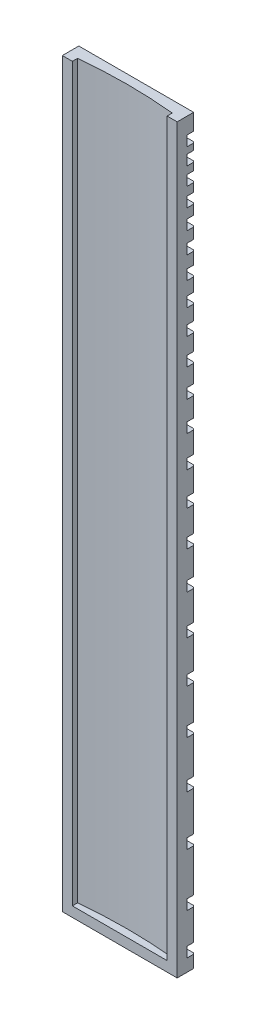
SolidWorks part; units mm, degrees
ref_plane "Front Plane" through (0, 0, 0) normal (0, 0, 1) x (1, 0, 0)
ref_plane "Top Plane" through (0, 0, 0) normal (0, 1, 0) x (1, 0, 0)
ref_plane "Right Plane" through (0, 0, 0) normal (1, 0, 0) x (0, 0, -1)
sketch "Sketch1" plane through (0, 0, 0) normal (0, 0, 1) x (1, 0, 0)
  line L0 (0, 464.91) -> (0, -53.7621) construction
  line L1 (207.2765, 0) -> (-181.268, 0) construction
  line L2 (23.8804, 464.91) -> (23.8804, -53.7621) construction
  line L3 (-23.8804, 464.91) -> (-23.8804, -53.7621) construction
  line L4 (16.5652, 464.91) -> (16.5652, -53.7621) construction
  line L5 (-16.5652, 464.91) -> (-16.5652, -53.7621) construction
  line L6 (-39.4637, 452.8091) -> (40.6786, 452.8091) construction
  line L7 (40.6786, 4) -> (-39.4637, 4) construction
  line L8 (-16.5652, 4) -> (-23.8804, 452.8091) construction
  line L9 (23.8804, 452.8091) -> (16.5652, 4) construction
  line L10 (-39.4637, 442.2134) -> (40.6786, 442.2134) construction
  line L11 (40.6786, 31.6398) -> (-39.4637, 31.6398) construction
  line L12 (40.6786, 430.9875) -> (-39.4637, 430.9875) construction
  line L13 (-39.4637, 455.3091) -> (40.6786, 455.3091)
  line L14 (-39.4637, 65.2793) -> (40.6786, 65.2793) construction
  line L15 (-39.4637, 364.0154) -> (40.6786, 364.0154) construction
  line L16 (-39.4637, 444.7134) -> (40.6786, 444.7134)
  line L17 (-39.4637, 61.2793) -> (40.6786, 61.2793)
  line L18 (-39.4637, 97.0308) -> (40.6786, 97.0308) construction
  line L19 (-39.4637, 93.0308) -> (40.6786, 93.0308)
  line L20 (40.6786, 127.0002) -> (-39.4637, 127.0002) construction
  line L21 (-39.4637, 67.7793) -> (40.6786, 67.7793)
  line L22 (-39.4637, 155.2875) -> (40.6786, 155.2875) construction
  line L23 (-39.4637, 366.5154) -> (40.6786, 366.5154)
  line L24 (40.6786, 181.9872) -> (-39.4637, 181.9872) construction
  line L25 (-39.4637, 99.5308) -> (40.6786, 99.5308)
  line L26 (-39.4637, 207.1884) -> (40.6786, 207.1884) construction
  line L27 (-39.4637, 151.2875) -> (40.6786, 151.2875)
  line L28 (40.6786, 230.9751) -> (-39.4637, 230.9751) construction
  line L29 (-39.4637, 157.7875) -> (40.6786, 157.7875)
  line L30 (-39.4637, 253.4267) -> (40.6786, 253.4267) construction
  line L31 (-39.4637, 203.1883) -> (40.6786, 203.1883)
  line L32 (40.6786, 274.6183) -> (-39.4637, 274.6183) construction
  line L33 (-39.4637, 209.6884) -> (40.6786, 209.6884)
  line L34 (-39.4637, 294.6205) -> (40.6786, 294.6205) construction
  line L35 (-39.4637, 249.4267) -> (40.6786, 249.4267)
  line L36 (40.6786, 313.5) -> (-39.4637, 313.5) construction
  line L37 (-39.4637, 255.9267) -> (40.6786, 255.9267)
  line L38 (-39.4637, 331.3199) -> (40.6786, 331.3199) construction
  line L39 (-39.4637, 290.6205) -> (40.6786, 290.6205)
  line L40 (40.6786, 348.1397) -> (-39.4637, 348.1397) construction
  line L41 (-39.4637, 297.1205) -> (40.6786, 297.1205)
  line L42 (-39.4637, 379.0001) -> (40.6786, 379.0001) construction
  line L43 (-39.4637, 327.3199) -> (40.6786, 327.3199)
  line L44 (40.6786, 393.1438) -> (-39.4637, 393.1437) construction
  line L45 (-39.4637, 333.8199) -> (40.6786, 333.8199)
  line L46 (-39.4637, 406.4936) -> (40.6786, 406.4936) construction
  line L47 (-39.4637, 360.0154) -> (40.6786, 360.0154)
  line L48 (40.6786, 419.0942) -> (-39.4637, 419.0942) construction
  line L49 (-39.4637, 381.5001) -> (40.6786, 381.5001)
  line L50 (-39.4637, 375.0001) -> (40.6786, 375.0001)
  line L51 (-39.4637, 408.9936) -> (40.6786, 408.9936)
  line L52 (-39.4637, 402.4936) -> (40.6786, 402.4936)
  line L53 (-39.4637, 438.2134) -> (40.6786, 438.2134)
  line L54 (-39.4637, 448.8091) -> (40.6786, 448.8091)
  line L55 (40.6786, 34.1398) -> (-39.4637, 34.1398)
  line L56 (40.6786, 433.4875) -> (-39.4637, 433.4875)
  line L57 (40.6786, 426.9875) -> (-39.4637, 426.9875)
  line L58 (40.6786, 415.0942) -> (-39.4637, 415.0942)
  line L59 (40.6786, 389.1438) -> (-39.4637, 389.1438)
  line L60 (40.6786, 129.5002) -> (-39.4637, 129.5002)
  line L61 (40.6786, 344.1397) -> (-39.4637, 344.1397)
  line L62 (40.6786, 184.4872) -> (-39.4637, 184.4872)
  line L63 (40.6786, 309.5) -> (-39.4637, 309.5)
  line L64 (40.6786, 233.4751) -> (-39.4637, 233.4751)
  line L65 (40.6786, 270.6183) -> (-39.4637, 270.6183)
  line L66 (40.6786, 277.1183) -> (-39.4637, 277.1183)
  line L67 (40.6786, 226.9751) -> (-39.4637, 226.9751)
  line L68 (40.6786, 316) -> (-39.4637, 316)
  line L69 (40.6786, 177.9872) -> (-39.4637, 177.9872)
  line L70 (40.6786, 350.6397) -> (-39.4637, 350.6397)
  line L71 (40.6786, 123.0002) -> (-39.4637, 123.0002)
  line L72 (40.6786, 395.6438) -> (-39.4637, 395.6438)
  line L73 (40.6786, 27.6398) -> (-39.4637, 27.6398)
  line L74 (40.6786, 421.5942) -> (-39.4637, 421.5942)
  line L75 (40.6786, 1.5) -> (-39.4637, 1.5)
  line L76 (40.6786, 8) -> (-39.4637, 8)
  line L77 (40.6786, 1.5) -> (40.6786, 8)
  line L78 (40.6786, 448.8091) -> (40.6786, 455.3091)
  line L79 (40.6786, 438.2134) -> (40.6786, 444.7134)
  line L80 (40.6786, 426.9875) -> (40.6786, 433.4875)
  line L81 (40.6786, 415.0942) -> (40.6786, 421.5942)
  line L82 (40.6786, 402.4936) -> (40.6786, 408.9936)
  line L83 (40.6786, 389.1438) -> (40.6786, 395.6438)
  line L84 (40.6786, 375.0001) -> (40.6786, 381.5001)
  line L85 (40.6786, 360.0154) -> (40.6786, 366.5154)
  line L86 (40.6786, 344.1397) -> (40.6786, 350.6397)
  line L87 (40.6786, 327.3199) -> (40.6786, 333.8199)
  line L88 (40.6786, 309.5) -> (40.6786, 316)
  line L89 (40.6786, 290.6205) -> (40.6786, 297.1205)
  line L90 (40.6786, 270.6183) -> (40.6786, 277.1183)
  line L91 (40.6786, 249.4267) -> (40.6786, 255.9267)
  line L92 (40.6786, 226.9751) -> (40.6786, 233.4751)
  line L93 (40.6786, 203.1883) -> (40.6786, 209.6884)
  line L94 (40.6786, 177.9872) -> (40.6786, 184.4872)
  line L95 (40.6786, 151.2875) -> (40.6786, 157.7875)
  line L96 (40.6786, 123.0002) -> (40.6786, 129.5002)
  line L97 (40.6786, 93.0308) -> (40.6786, 99.5308)
  line L98 (40.6786, 61.2793) -> (40.6786, 67.7793)
  line L99 (40.6786, 27.6398) -> (40.6786, 34.1398)
  line L100 (-39.4637, 1.5) -> (-39.4637, 8)
  line L101 (-39.4637, 448.8091) -> (-39.4637, 455.3091)
  line L102 (-39.4637, 438.2134) -> (-39.4637, 444.7134)
  line L103 (-39.4637, 426.9875) -> (-39.4637, 433.4875)
  line L104 (-39.4637, 415.0942) -> (-39.4637, 421.5942)
  line L105 (-39.4637, 402.4936) -> (-39.4637, 408.9936)
  line L106 (-39.4637, 389.1438) -> (-39.4637, 395.6438)
  line L107 (-39.4637, 375.0001) -> (-39.4637, 381.5001)
  line L108 (-39.4637, 360.0154) -> (-39.4637, 366.5154)
  line L109 (-39.4637, 344.1397) -> (-39.4637, 350.6397)
  line L110 (-39.4637, 327.3199) -> (-39.4637, 333.8199)
  line L111 (-39.4637, 309.5) -> (-39.4637, 316)
  line L112 (-39.4637, 290.6205) -> (-39.4637, 297.1205)
  line L113 (-39.4637, 270.6183) -> (-39.4637, 277.1183)
  line L114 (-39.4637, 249.4267) -> (-39.4637, 255.9267)
  line L115 (-39.4637, 226.9751) -> (-39.4637, 233.4751)
  line L116 (-39.4637, 203.1883) -> (-39.4637, 209.6884)
  line L117 (-39.4637, 177.9872) -> (-39.4637, 184.4872)
  line L118 (-39.4637, 151.2875) -> (-39.4637, 157.7875)
  line L119 (-39.4637, 123.0002) -> (-39.4637, 129.5002)
  line L120 (-39.4637, 93.0308) -> (-39.4637, 99.5308)
  line L121 (-39.4637, 61.2793) -> (-39.4637, 67.7793)
  line L122 (-39.4637, 27.6398) -> (-39.4637, 34.1398)
  dimension "D7" = 2.5
  dimension "D31" = 6.5
  dimension "D1" = 23.8804
  dimension "D2" = 23.8804
  dimension "D3" = 16.5652
  dimension "D4" = 16.5652
  dimension "D5" = 452.8091
  dimension "D6" = 4
  dimension "D9" = 6.5
  dimension "D10" = 31.6398
  dimension "D11" = 65.2793
  dimension "D12" = 97.0308
  dimension "D13" = 127.0002
  dimension "D14" = 155.2875
  dimension "D15" = 181.9872
  dimension "D16" = 207.1884
  dimension "D17" = 230.9751
  dimension "D18" = 253.4267
  dimension "D19" = 274.6183
  dimension "D20" = 294.6205
  dimension "D21" = 313.5
  dimension "D22" = 331.3199
  dimension "D23" = 348.1397
  dimension "D24" = 442.2134
  dimension "D25" = 430.9875
  dimension "D26" = 419.0942
  dimension "D27" = 406.4936
  dimension "D28" = 393.1438
  dimension "D29" = 379.0001
  dimension "D30" = 364.0154
  dimension "D33" = 6.5
  dimension "D8" = 2.5
  dimension "D32" = 2.5
sketch "Sketch2" plane through (0, 0, 0) normal (0, 0, 1) x (1, 0, 0)
  line L0 (30.163, 490.1178) -> (30.163, -68.1918) construction
  line L1 (-30.163, 490.1178) -> (-30.163, -68.1918) construction
  line L2 (0, 464.91) -> (0, -53.7621) construction
  line L3 (36.563, -68.1918) -> (36.563, 490.1178) construction
  line L4 (-36.563, 490.1178) -> (-36.563, -68.1918) construction
  line L5 (-36.563, 0) -> (36.563, 0)
  line L6 (207.2765, 0) -> (-181.268, 0) construction
  line L7 (36.563, 0) -> (36.563, 465.7035)
  line L8 (36.563, 465.7035) -> (-36.563, 465.7035)
  line L9 (-36.563, 465.7035) -> (-36.563, 0)
  dimension "D1" = 30.163
  dimension "D2" = 30.163
  dimension "D3" = 6.4
  dimension "D4" = 6.4
extrude "Boss-Extrude1" add sketch "Sketch2" along normal blind 12.8
sketch "Sketch3" plane through (0, 0, 0) normal (0, 1, 0) x (1, 0, 0)
  line L0 (38.7043, 0) -> (-38.1623, 0) construction
  line L1 (39.8582, -6.4) -> (-38.1623, -6.4) construction
  line L2 (-36.563, -12.8) -> (36.563, -12.8) construction
  line L3 (38.7043, -311.2) -> (0, -311.2) construction
  line L4 (30.163, -12.8) -> (30.163, -7.8961)
  line L5 (-30.163, -12.8) -> (-30.163, -7.8961)
  arc A0 (30.163, -7.8961) -> (-30.163, -7.8961) centre (0, -311.2) ccw
  dimension "D1" = 6.4
  dimension "D2" = 304.8
  dimension "D3" = 30.163
  dimension "D4" = 30.163
extrude "Cut-Extrude3" cut sketch "Sketch3" against normal through all and the other way through all flip side to cut
sketch "Sketch4" plane through (0, 0, 0) normal (0, 0, 1) x (1, 0, 0)
  line L1 (-36.563, 0) -> (36.563, 0)
  line L2 (-36.563, 0) -> (-36.563, -6.4)
  line L3 (-36.563, -6.4) -> (36.563, -6.4)
  line L4 (36.563, 0) -> (36.563, -6.4)
  dimension "D1" = 6.4
extrude "Boss-Extrude3" add sketch "Sketch4" along normal blind 12.8
ref_plane "Plane1" through (0, 0, 4) normal (0, 0, 1) x (1, 0, 0)
sketch "Sketch6" plane through (0, 0, 4) normal (0, 0, 1) x (1, 0, 0)
  line L4 (-23.9019, 235.1951) -> (-49.3974, 235.1951)
  line L26 (88.4047, 229.6) -> (-88.9547, 229.6) construction
  line L27 (-36.563, -6.4) -> (36.563, -6.4) construction
  line L28 (38.8194, 235.4451) -> (23.9282, 235.4451)
  line L29 (-23.9282, 235.4451) -> (-49.3974, 235.4451)
  line L36 (-43.0535, 233.9982) -> (-37.9136, 235.1951) construction
  line L37 (18.1118, 248.2421) -> (-43.0535, 248.2421) construction
  line L38 (38.8194, 235.1951) -> (23.9019, 235.1951)
  line L39 (0, 221.5497) -> (0, 263.5634) construction
  line L40 (38.8194, 234.9451) -> (23.8757, 234.9451)
  line L41 (-23.8757, 234.9451) -> (-49.3974, 234.9451)
  line L42 (38.8194, 235.4451) -> (38.8194, 471.8117)
  line L43 (38.8194, 471.8117) -> (-37.9136, 471.8117)
  line L44 (-37.9136, 471.8117) -> (-49.3974, 235.4451)
  spline S0 degree 2 poles (0, 247.3679) (-10.7842, 247.3592) (-21.1489, 244.7709) knots 0 0 0 1 1 1
  spline S1 degree 3 poles (-21.1489, 244.7709) (-37.3576, 240.3411) (-4.2165, 239.3715) (-23.9019, 235.1951) knots 0 0 0 0 1 1 1 1
  spline S2 degree 3 poles (21.1489, 244.7709) (37.3576, 240.3411) (4.2165, 239.3715) (23.9019, 235.1951) knots 0 0 0 0 1 1 1 1
  spline S3 degree 2 poles (0, 247.3679) (10.7842, 247.3592) (21.1489, 244.7709) knots 0 0 0 1 1 1
  spline S4 degree 1 poles (21.2121, 245.0128) (23.9282, 235.4451) knots 0 0 1 1 construction
  spline S5 degree 1 poles (0, 247.6179) (21.2121, 245.0128) knots 0 0 1 1 construction
  spline S6 degree 1 poles (0, 247.6179) (-21.2121, 245.0128) knots 0 0 1 1 construction
  spline S7 degree 1 poles (-21.2121, 245.0128) (-23.9282, 235.4451) knots 0 0 1 1 construction
  spline S8 degree 3 poles (23.9282, 235.4451) (23.6348, 235.5075) (23.0312, 235.6397) (21.9693, 235.8882) (20.8094, 236.1907) (19.6992, 236.5347) (18.5615, 236.9688) (17.9094, 237.3695) (17.6986, 237.6707) (17.6829, 237.7979) (17.739, 237.9582) (18.0148, 238.258) (18.7071, 238.6703) (19.903, 239.162) (21.7672, 239.8167) (23.7279, 240.4802) (25.2001, 241.2084) (25.8203, 241.7115) (26.0573, 242.2461) (25.9835, 242.8528) (25.4979, 243.3457) (24.6357, 243.835) (23.7639, 244.2108) (22.8283, 244.5374) (21.9574, 244.8043) (21.4557, 244.9462) (21.2121, 245.0128) knots -0.000055 -0.000055 -0.000055 -0.000055 0.015564 0.031183 0.062421 0.09366 0.124898 0.187374 0.218612 0.24985 0.281088 0.312326 0.374802 0.437278 0.499755 0.624707 0.687183 0.749659 0.780897 0.812135 0.874612 0.90585 0.937088 0.968326 0.983945 0.999564 0.999564 0.999564 0.999564
  spline S9 degree 2 poles (21.2121, 245.0128) (10.816, 247.6092) (0, 247.6179) knots -0.000009 -0.000009 -0.000009 1.000129 1.000129 1.000129
  spline S10 degree 2 poles (0, 247.6179) (-10.816, 247.6092) (-21.2121, 245.0128) knots -0.000009 -0.000009 -0.000009 1.000129 1.000129 1.000129
  spline S11 degree 3 poles (-21.2121, 245.0128) (-21.4557, 244.9462) (-21.9574, 244.8043) (-22.8283, 244.5374) (-23.7639, 244.2108) (-24.6357, 243.835) (-25.4979, 243.3457) (-25.9835, 242.8528) (-26.0573, 242.2461) (-25.8203, 241.7115) (-25.2001, 241.2084) (-23.7279, 240.4802) (-21.7672, 239.8167) (-19.903, 239.162) (-18.7071, 238.6703) (-18.0148, 238.258) (-17.739, 237.9582) (-17.6829, 237.7979) (-17.6986, 237.6707) (-17.9094, 237.3695) (-18.5615, 236.9688) (-19.6992, 236.5347) (-20.8094, 236.1907) (-21.9693, 235.8882) (-23.0312, 235.6397) (-23.6348, 235.5075) (-23.9282, 235.4451) knots -0.000055 -0.000055 -0.000055 -0.000055 0.015564 0.031183 0.062421 0.09366 0.124898 0.187374 0.218612 0.24985 0.312326 0.374802 0.499755 0.562231 0.624707 0.687183 0.718421 0.749659 0.780897 0.812135 0.874612 0.90585 0.937088 0.968326 0.983945 0.999564 0.999564 0.999564 0.999564
  spline S12 degree 1 poles (21.0857, 244.529) (23.8757, 234.9451) knots 0 0 1 1 construction
  spline S13 degree 1 poles (0, 247.1179) (21.0857, 244.529) knots 0 0 1 1 construction
  spline S14 degree 1 poles (0, 247.1179) (-21.0857, 244.529) knots 0 0 1 1 construction
  spline S15 degree 1 poles (-21.0857, 244.529) (-23.8757, 234.9451) knots 0 0 1 1 construction
  spline S16 degree 3 poles (23.8757, 234.9451) (23.5787, 235.0082) (22.9678, 235.1413) (21.8899, 235.3927) (20.708, 235.6996) (19.5654, 236.0516) (18.6696, 236.3915) (18.0001, 236.7235) (17.5327, 237.0576) (17.2381, 237.4209) (17.1559, 237.8621) (17.323, 238.2556) (17.723, 238.6714) (18.4869, 239.1197) (19.7184, 239.6272) (21.1286, 240.1222) (22.5715, 240.6172) (23.8953, 241.1217) (24.9459, 241.6374) (25.4407, 242.0735) (25.5382, 242.3329) (25.5244, 242.4959) (25.3759, 242.7409) (25.0138, 243.0449) (24.423, 243.3812) (23.5911, 243.7412) (22.6782, 244.0603) (21.822, 244.3229) (21.3261, 244.4633) (21.0857, 244.529) knots 0.000055 0.000055 0.000055 0.000055 0.015686 0.031317 0.062579 0.093841 0.125102 0.156364 0.187626 0.218888 0.25015 0.281412 0.312674 0.375197 0.437721 0.500245 0.562768 0.625292 0.687816 0.75034 0.781601 0.812863 0.844125 0.875387 0.906649 0.937911 0.969173 0.984804 1.000434 1.000434 1.000434 1.000434
  spline S17 degree 2 poles (21.0857, 244.529) (10.7523, 247.1092) (0, 247.1179) knots 0.000009 0.000009 0.000009 0.99987 0.99987 0.99987
  spline S18 degree 2 poles (0, 247.1179) (-10.7523, 247.1092) (-21.0857, 244.529) knots 0.000009 0.000009 0.000009 0.99987 0.99987 0.99987
  spline S19 degree 3 poles (-21.0857, 244.529) (-21.3261, 244.4633) (-21.822, 244.3229) (-22.6782, 244.0603) (-23.5911, 243.7412) (-24.423, 243.3812) (-25.0138, 243.0449) (-25.3759, 242.7409) (-25.5244, 242.4959) (-25.5382, 242.3329) (-25.4407, 242.0735) (-24.9459, 241.6374) (-23.8953, 241.1217) (-22.5715, 240.6172) (-21.1286, 240.1222) (-19.7184, 239.6272) (-18.4869, 239.1197) (-17.723, 238.6714) (-17.323, 238.2556) (-17.1559, 237.8621) (-17.2381, 237.4209) (-17.5327, 237.0576) (-18.0001, 236.7235) (-18.6696, 236.3915) (-19.5654, 236.0516) (-20.708, 235.6996) (-21.8899, 235.3927) (-22.9678, 235.1413) (-23.5787, 235.0082) (-23.8757, 234.9451) knots 0.000055 0.000055 0.000055 0.000055 0.015686 0.031317 0.062579 0.093841 0.125102 0.156364 0.187626 0.218888 0.25015 0.312674 0.375197 0.437721 0.500245 0.562768 0.625292 0.687816 0.719078 0.75034 0.781601 0.812863 0.844125 0.875387 0.906649 0.937911 0.969173 0.984804 1.000434 1.000434 1.000434 1.000434
  dimension "D1" = 236
  dimension "D2" = 0.25
  dimension "D3" = 0.25
chamfer "Chamfer5" distance 0.7 angle 45 4 edges at (0, 465.7035, 0) (-36.563, 229.6518, 0) (0, -6.4, 0) (36.563, 229.6518, 0)
extrude "Cut-Extrude4" cut sketch "Sketch1" along normal blind 5
ref_plane "Plane2" through (0, 0, 12.8) normal (0, 0, 1) x (1, 0, 0)
sketch "Sketch7" plane through (0, 0, 12.8) normal (0, 0, 1) x (1, 0, 0)
  line L1 (-36.563, 465.7035) -> (36.563, 465.7035)
  line L2 (-36.563, 465.7035) -> (-36.563, -6.4)
  line L3 (-36.563, -6.4) -> (36.563, -6.4)
  line L4 (36.563, 465.7035) -> (36.563, -6.4)
extrude "Cut-Extrude7" cut sketch "Sketch7" against normal blind 1.6
